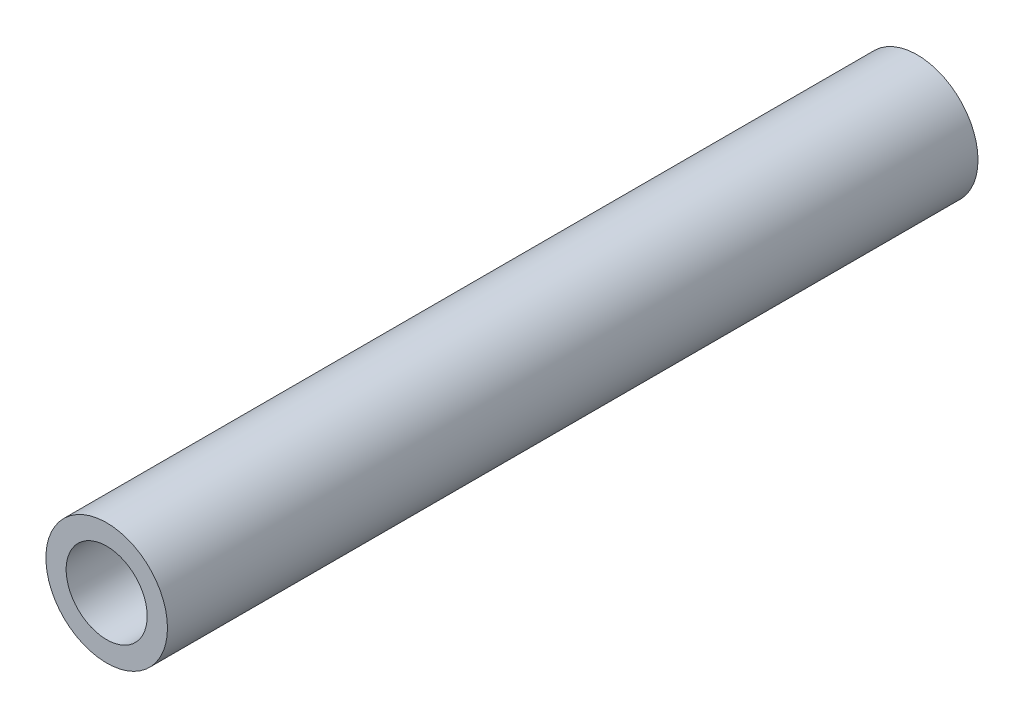
SolidWorks part; units mm, degrees
material "C-Fibra di vetro"
ref_plane "Piano frontale" through (0, 0, 0) normal (0, 0, 1) x (1, 0, 0)
ref_plane "Piano superiore" through (0, 0, 0) normal (0, 1, 0) x (1, 0, 0)
ref_plane "Piano destro" through (0, 0, 0) normal (1, 0, 0) x (0, 0, -1)
sketch "Schizzo1" plane through (0, 0, 33.4279) normal (0, 0, 1) x (1, 0, 0)
  circle A0 centre (230, -26.5864) radius 3
  circle A1 centre (230, -26.5864) radius 2
  dimension "D1" = 1
  dimension "D2" = 6
extrude "Estrusione-Estrusione1" add sketch "Schizzo1" against normal up to surface (40 mm away)
